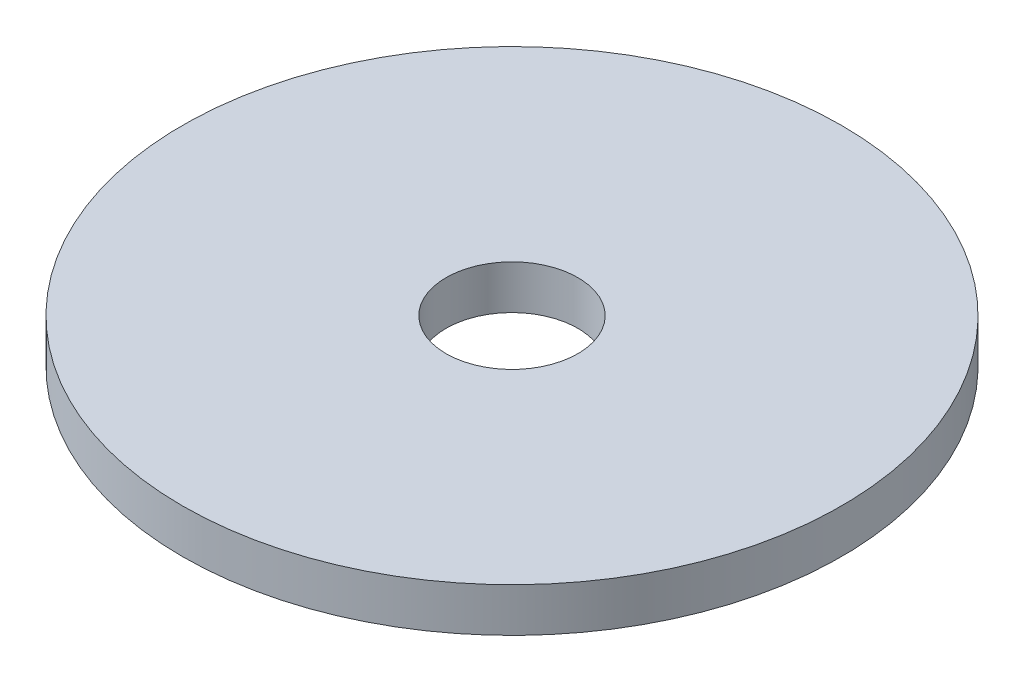
SolidWorks part; units mm, degrees
ref_plane "Front Plane" through (0, 0, 0) normal (0, 0, 1) x (1, 0, 0)
ref_plane "Top Plane" through (0, 0, 0) normal (0, 1, 0) x (1, 0, 0)
ref_plane "Right Plane" through (0, 0, 0) normal (1, 0, 0) x (0, 0, -1)
sketch "Sketch1" plane through (0, 0, 0) normal (0, 1, 0) x (1, 0, 0)
  circle A0 centre (0, 0) radius 7.5
  circle A1 centre (0, 0) radius 1.5
  dimension "D1" = 15
  dimension "D2" = 1.5
extrude "Boss-Extrude1" add sketch "Sketch1" along normal blind 1
